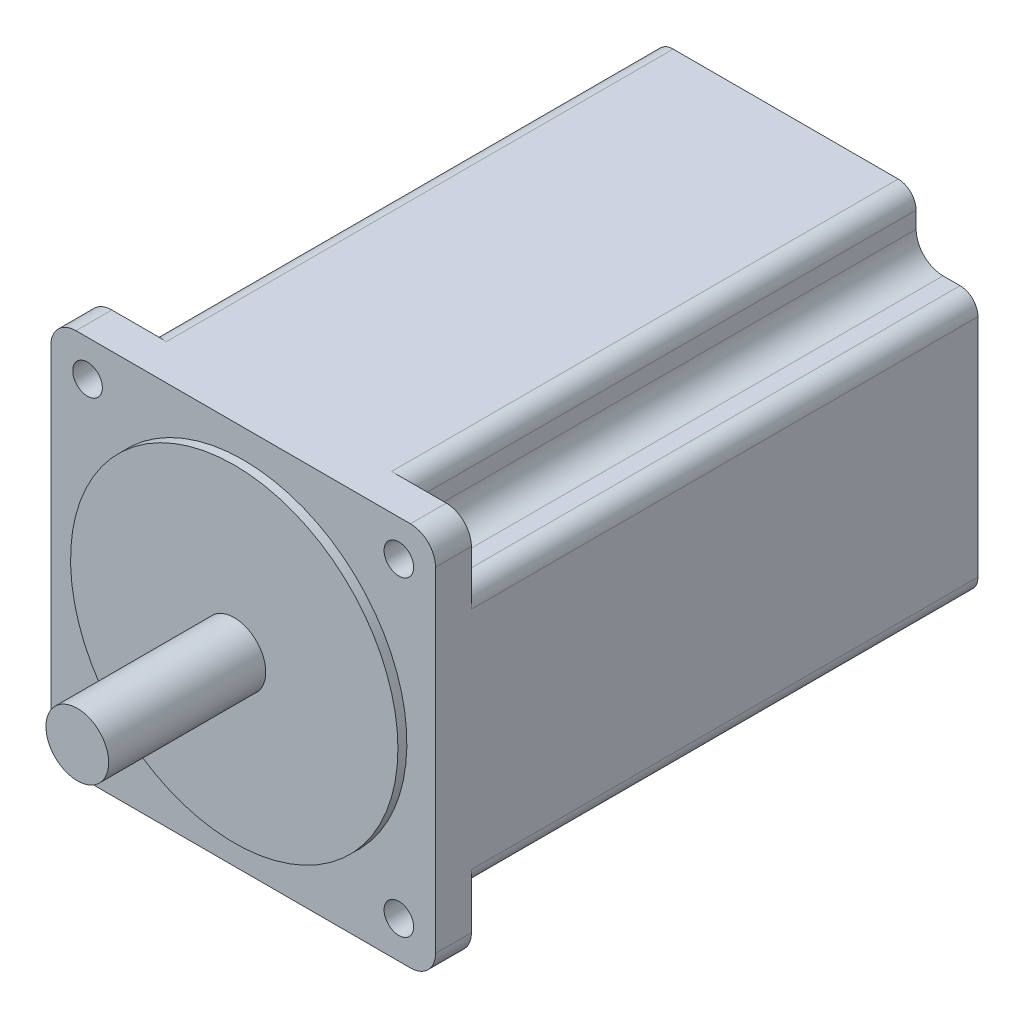
SolidWorks part; units mm, degrees
ref_plane "Płaszczyzna przednia" through (0, 0, 0) normal (0, 0, 1) x (1, 0, 0)
ref_plane "Płaszczyzna górna" through (0, 0, 0) normal (0, 1, 0) x (1, 0, 0)
ref_plane "Płaszczyzna prawa" through (0, 0, 0) normal (1, 0, 0) x (0, 0, -1)
ref_plane "Płaszczyzna3" through (0, -55, 0) normal (0, 1, 0) x (1, 0, 0)
ref_plane "Płaszczyzna4" through (0, 0, -121) normal (0, 0, 1) x (1, 0, 0)
sketch "Szkic7" plane through (0, -55, 0) normal (0, 1, 0) x (-1, 0, 0)
  line L0 (10.8, -93.4) -> (10.8, -115)
  line L1 (10.8, -115) -> (-10.8, -115)
  line L2 (-10.8, -115) -> (-10.8, -93.4)
  line L3 (-10.8, -93.4) -> (10.8, -93.4)
extrude "Dodanie-wyciągnięcie5" add sketch "Szkic7" along normal blind 12
sketch "Szkic8" plane through (0, -43, 0) normal (0, 1, 0) x (-1, 0, 0)
  line L0 (42.9, -115) -> (-42.9, -115)
  line L1 (-42.9, -115) -> (-42.9, 0)
  line L2 (-42.9, 0) -> (42.9, 0)
  line L3 (42.9, 0) -> (42.9, -115)
extrude "Dodanie-wyciągnięcie6" add sketch "Szkic8" along normal blind 85.8
sketch "Szkic9" plane through (0, 0, -121) normal (0, 0, -1) x (-1, 0, 0)
  line L0 (42.9, 42.8) -> (42.9, -36.1883)
  line L1 (42.9, -36.1883) -> (-42.9, -36.1883)
  line L2 (-42.9, -36.1883) -> (-42.9, 42.8)
  line L3 (-42.9, 42.8) -> (42.9, 42.8)
  line L5 (-42.9, 42.8) -> (42.9, 42.8) construction
extrude "Dodanie-wyciągnięcie7" add sketch "Szkic9" against normal blind 7
sketch "Szkic10" plane through (-42.9, 0, 0) normal (-1, 0, 0) x (0, 0, 1)
  line L0 (-121, -45.7464) -> (-8, -45.7464)
  line L1 (-8, -45.7464) -> (-8, -29.1)
  line L2 (-8, -29.1) -> (-121, -29.1)
  line L3 (-121, -29.1) -> (-121, -45.7464)
  line L4 (0, 42.8) -> (0, -43) construction
  line L5 (-121, -36.1883) -> (-121, 42.8) construction
  dimension "D1" = 8
extrude "Wytnij-wyciągnięcie3" cut sketch "Szkic10" against normal blind 13.8
sketch "Szkic11" plane through (0, -43, 0) normal (0, -1, 0) x (1, 0, 0)
  line L0 (42.9, -121) -> (42.9, -8)
  line L1 (42.9, -8) -> (29.1, -8)
  line L2 (29.1, -8) -> (29.1, -121)
  line L3 (29.1, -121) -> (42.9, -121)
extrude "Wytnij-wyciągnięcie4" cut sketch "Szkic11" against normal blind 13.8
sketch "Szkic12" plane through (42.9, 0, 0) normal (1, 0, 0) x (0, 0, -1)
  line L0 (121, 42.9) -> (8, 42.9)
  line L1 (8, 42.9) -> (8, 29.1)
  line L2 (8, 29.1) -> (121, 29.1)
  line L3 (121, 29.1) -> (121, 42.9)
extrude "Wytnij-wyciągnięcie5" cut sketch "Szkic12" against normal blind 13.8
sketch "Szkic13" plane through (0, 42.8, 0) normal (0, 1, 0) x (-1, 0, 0)
  line L0 (42.9, -121) -> (42.9, -8)
  line L1 (42.9, -8) -> (29.1, -8)
  line L2 (29.1, -8) -> (29.1, -121)
  line L3 (29.1, -121) -> (42.9, -121)
  line L4 (42.9, -121) -> (-29.1, -121) construction
  line L5 (-42.9, -8) -> (-29.1, -8) construction
extrude "Wytnij-wyciągnięcie6" cut sketch "Szkic13" against normal blind 13.8
sketch "Szkic14" plane through (0, 0, 0) normal (0, 0, 1) x (1, 0, 0)
  circle A0 centre (0, 0) radius 36.51
extrude "Dodanie-wyciągnięcie8" add sketch "Szkic14" along normal blind 2
hole_wizard "Otwór pod śrubę M121" positions "Szkic16" profile "Szkic15" hole size "M12" standard "Ansi Metric"
sketch "Szkic16" plane through (0, 0, 2) normal (0, 0, 1) x (1, 0, 0)
  point P0 (0, 0)
sketch "Szkic15" plane through (0, 0, 2) normal (1, 0, 0) x (0, -1, 0)
  line L0 (0, 0) -> (0, 2)
  line L1 (0, 2) -> (7.025, 2)
  line L2 (7.025, 2) -> (7.025, 0)
  line L5 (7.025, 0) -> (0, 0)
  line L10 (0, 2) -> (-7.025, 2) construction
  line L11 (0, -6.35) -> (0, 107.95) construction
  dimension "Średnica otworu" = 14.05
  dimension "Głębokość otworu" = 2
  dimension "Kąt wiertła" = 180
sketch "Szkic17" plane through (0, 0, 0) normal (0, 1, 0) x (1, 0, 0)
  line L0 (7, 0) -> (0, 0)
  line L1 (0, 0) -> (0, -37)
  line L2 (0, -37) -> (7, -37)
  line L3 (7, -37) -> (7, 0)
  line L4 (0, 0) -> (0, -37) construction
revolve "Obrót1" add sketch "Szkic17" angle 360 about L4
hole_wizard "Otwór Ø6.6 (6.6)1" positions "Szkic20" profile "Szkic19" hole size "Ø6.6" standard "Ansi Metric"
sketch "Szkic20" plane through (0, 0, -8) normal (0, 0, -1) x (-1, 0, 0)
  point P0 (34.7189, -34.7189)
  point P1 (-34.7189, -34.7189)
  point P2 (-34.7189, 34.7189)
  point P3 (34.7189, 34.7189)
sketch "Szkic19" plane through (-34.7189, -34.7189, -8) normal (1, 0, 0) x (0, 1, 0)
  line L0 (0, 0) -> (0, 45)
  line L1 (0, 45) -> (3.3, 45)
  line L2 (3.3, 45) -> (3.3, 0)
  line L5 (3.3, 0) -> (0, 0)
  line L11 (0, -6.35) -> (0, 107.95) construction
  dimension "Średnica otworu na wylot" = 6.6
  dimension "Głębokość otworu na wylot" = 45
fillet "Zaokrąglenie1" radius 4 8 edges at (29.1, -43, -61.5) (29.1, 42.8, -64.5) (-42.9, -29.1, -64.5) (-42.9, 29, -64.5) (-29.1, 42.8, -64.5) (42.9, -29.2, -64.5) (42.9, 29.1, -64.5) (-29.1, -43, -61.5)
fillet "Zaokrąglenie2" radius 5.6 4 edges at (42.9, -43, -4) (42.9, 42.8, -4) (-42.9, 42.8, -4) (-42.9, -43, -4)
fillet "Zaokrąglenie3" radius 6 4 edges at (-29.1, -29.1, -64.5) (29.1, 29.1, -64.5) (-29.1, 29, -64.5) (29.1, -29.2, -64.5)
